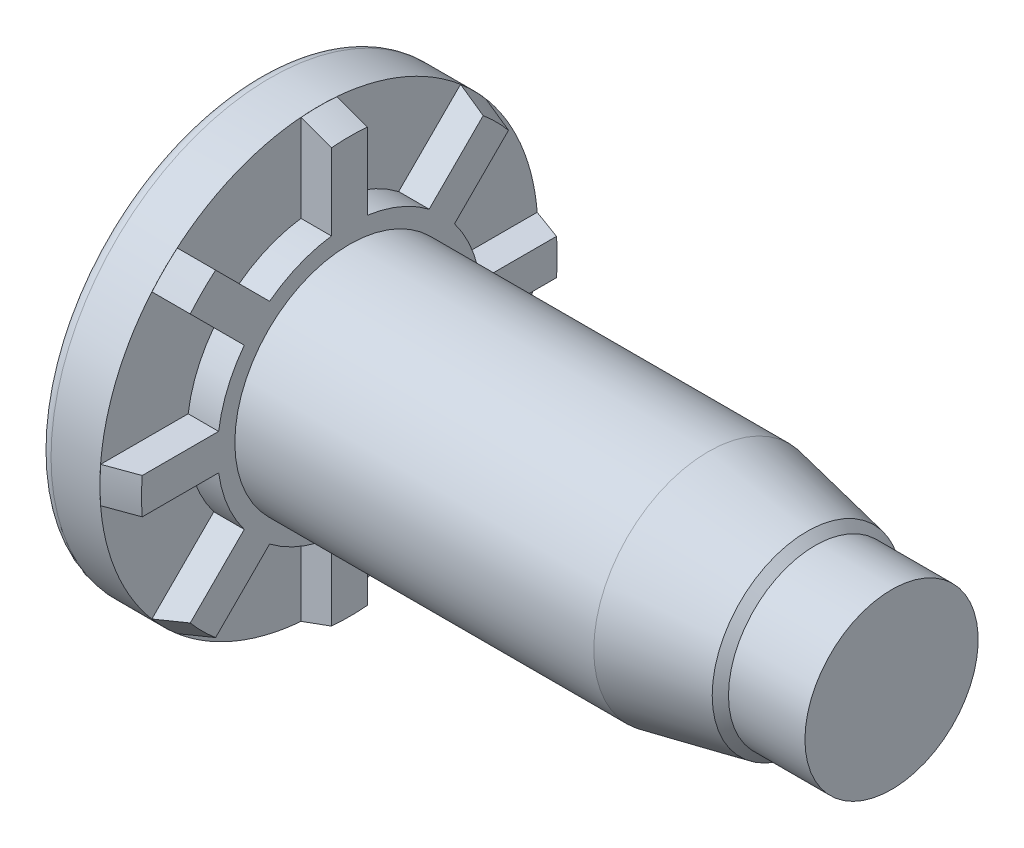
SolidWorks part; units mm, degrees
revolve "BaseBody" add sketch "BodySke" angle 360 about L6
sketch "BodySke" plane through (0, 0, 0) normal (0, 0, 1) x (1, 0, 0)
  line L0 (-2.13, 7.224) -> (-2.13, 0)
  line L1 (1.065, 7.2608) -> (1.065, 4)
  line L2 (0.0025, 7.6475) -> (1.065, 7.2608)
  line L3 (1.065, 4) -> (13.6, 4)
  line L4 (13.6, 4) -> (17.0455, 3.3095)
  line L5 (20, 0) -> (-2.13, 0)
  line L6 (0, 0) -> (50.554, 0) construction
  line L7 (17.33, 3.025) -> (20, 3.025)
  line L8 (17.33, 3.025) -> (17.0455, 3.3095)
  line L9 (-1.704, 7.65) -> (0, 7.65)
  line L10 (0.0025, 7.6475) -> (0, 7.6475)
  line L11 (1.25, 19.05) -> (1.25, -3.175) construction
  line L12 (0, 7.6475) -> (0, 7.65)
  line L13 (20, 3.025) -> (20, 0)
  arc A0 (-2.13, 7.224) -> (-1.704, 7.65) centre (-1.704, 7.224) cw
  dimension "Fillet_rad" = 0.426
  dimension "T_dim" = 2.13
  dimension "H_dia" = 15.3
  dimension "D2" = 0.0025
  dimension "D3" = 0.0025
  dimension "Advance" = 1.25
  dimension "D1" = 20
  dimension "Clinch_ht" = 1.065
  dimension "Dog_len" = 2.67
  dimension "Length" = 20
  dimension "Dog_dia" = 6.05
  dimension "D4" = 45
  dimension "Diameter" = 8
  dimension "Thread_trans" = 3.73
  dimension "Minor_dia" = 6.619
cosmetic thread "ThreadCosmetic" [suppressed] parameters "Thread_length"=13.7455, "Thread_minor"=6.619
ref_plane "Plane1" through (0, 0, 0) normal (0, 0, 1) x (1, 0, 0)
ref_plane "Plane2" through (0, 0, 0) normal (0, 1, 0) x (1, 0, 0)
ref_plane "Plane3" through (0, 0, 0) normal (1, 0, 0) x (0, 0, -1)
sketch "ThdSchSke" plane through (0, 0, 0) normal (0, 0, 1) x (1, 0, 0)
  line L0 (3.3, -3.3095) -> (2.8165, -4)
  line L1 (3.3, -3.3095) -> (3.7835, -4)
  line L2 (3.7835, -4) -> (3.7835, -5)
  line L3 (-3.175, 0) -> (5.1513, 0) construction
  line L4 (0, -7.65) -> (0, 7.65) construction
  line L5 (3.7835, -5) -> (2.8165, -5)
  line L6 (2.8165, -5) -> (2.8165, -4)
  line L7 (21.3518, 6.5809) -> (21.3518, 1.1961) construction
  dimension "Diameter" = 8
  dimension "Thread_minor" = 6.619
  dimension "Start" = 3.3
revolve "ThreadSchematic" [suppressed] cut sketch "ThdSchSke" angle 360 about L3
pattern_linear "ThdSchPat" [suppressed]
sketch "RibCutSke" plane through (1.065, 1.7944, -0.091) normal (1, 0, 0) x (0, 0, -1)
  line L0 (0.5348, 2.7713) -> (0.5348, 5.83)
  line L1 (2.695, 1.8765) -> (4.8578, 4.0393)
  line L2 (0.5348, 2.1564) -> (0.5348, 2.4006) construction
  line L3 (-0.091, -1.7944) -> (-0.091, 5.0239) construction
  line L4 (-0.091, -1.7944) -> (0.5348, 2.1564) construction
  line L5 (-0.091, -1.7944) -> (2.2602, 1.4417) construction
  line L6 (2.2602, 1.4417) -> (2.4379, 1.6194) construction
  arc A1 (2.695, 1.8765) -> (0.5348, 2.7713) centre (-0.091, -1.7944) ccw
  arc A2 (4.8578, 4.0393) -> (0.5348, 5.83) centre (-0.091, -1.7944) ccw
  circle A3 centre (-0.091, -1.7944) radius 7.2608 construction
  circle A4 centre (-0.091, -1.7944) radius 4 construction
  dimension "Rib_root_half_angle" = 9
  dimension "Rib_root_gap_angle" = 27
  dimension "Angle" = 45
extrude "RibCut" cut sketch "RibCutSke" against normal blind 1.065
pattern_circular "RibCutsPat" count 8 every 45 about axis through (0, 0, 0) along (1, 0, 0) of "RibCut"
equation "' \"Length@BodySke\" = 20"
equation "' \"H_dia@BodySke\" = 15.3"
equation "' \"Start@ThdSchSke\" = 3.3"
equation "' \"T_dim@BodySke\" = 2.13"
equation "' \"Dog_dia@BodySke\" = 6.05"
equation "' \"Dog_len@BodySke\" = 2.67"
equation "' \"Thread_trans@BodySke\" = 3.73"
equation "' \"Diameter@BodySke\" = 8"
equation "' \"Minor_dia@BodySke\" =  6.619"
equation "' \"Minor_dia@BodySke\" = 6.619"
equation "' \"Advance@BodySke\" = 1.25"
equation "\"Fillet_rad@BodySke\" =  \"T_dim@BodySke\" * 0.2"
equation "\"Clinch_ht@BodySke\" = \"T_dim@BodySke\" * 0.5"
equation "\"Num_ribs@RibCutsPat\" = 8"
equation "\"Angle@RibCutSke\" =\"Angle@RibCutsPat\""
equation "\"Rib_root_half_angle@RibCutSke\" = \"Angle@RibCutSke\" / 5"
equation "\"Rib_root_gap_angle@RibCutSke\" = \"Angle@RibCutSke\" - (2 * \"Rib_root_half_angle@RibCutSke\" )"
equation "\"Rib_root_dia@RibCutSke\" = \"Diameter@BodySke\""
equation "\"Inner_dia@RibCutSke\" = \"Diameter@BodySke\" + ( \"H_dia@BodySke\" - \"Diameter@BodySke\" ) / 6"
equation "\"Outer_dia@RibCutSke\" = \"H_dia@BodySke\""
equation "\"Depth@RibCut\" = \"Clinch_ht@BodySke\""
equation "\"Thread_length@ThreadCosmetic\" = \"Length@BodySke\" - \"Start@ThdSchSke\"  - \"Dog_len@BodySke\"  - ( \"Minor_dia@BodySke\" - \"Dog_dia@BodySke\" ) / 2"
equation "\"Thread_minor@ThreadCosmetic\" = \"Minor_dia@BodySke\""
equation "\"Thread_minor@ThdSchSke\" = \"Minor_dia@BodySke\""
equation "\"Diameter@ThdSchSke\" = \"Diameter@BodySke\""
equation "\"Overcut@ThdSchSke\" = \"Diameter@BodySke\" * 1.25"
equation "\"Num_threads@ThdSchPat\" = int( \"Thread_length@ThreadCosmetic\" / \"Advance@BodySke\" + 0.999 )  + 1"
equation "\"Advance@ThdSchPat\" = \"Thread_length@ThreadCosmetic\" /  (\"Num_threads@ThdSchPat\" - 1) 'relax it"
equation "\"Num_threads@ThdSchPat\" = \"Num_threads@ThdSchPat\" - sgn( \"Num_threads@ThdSchPat\" - 1) '---chamfered tips only---"
